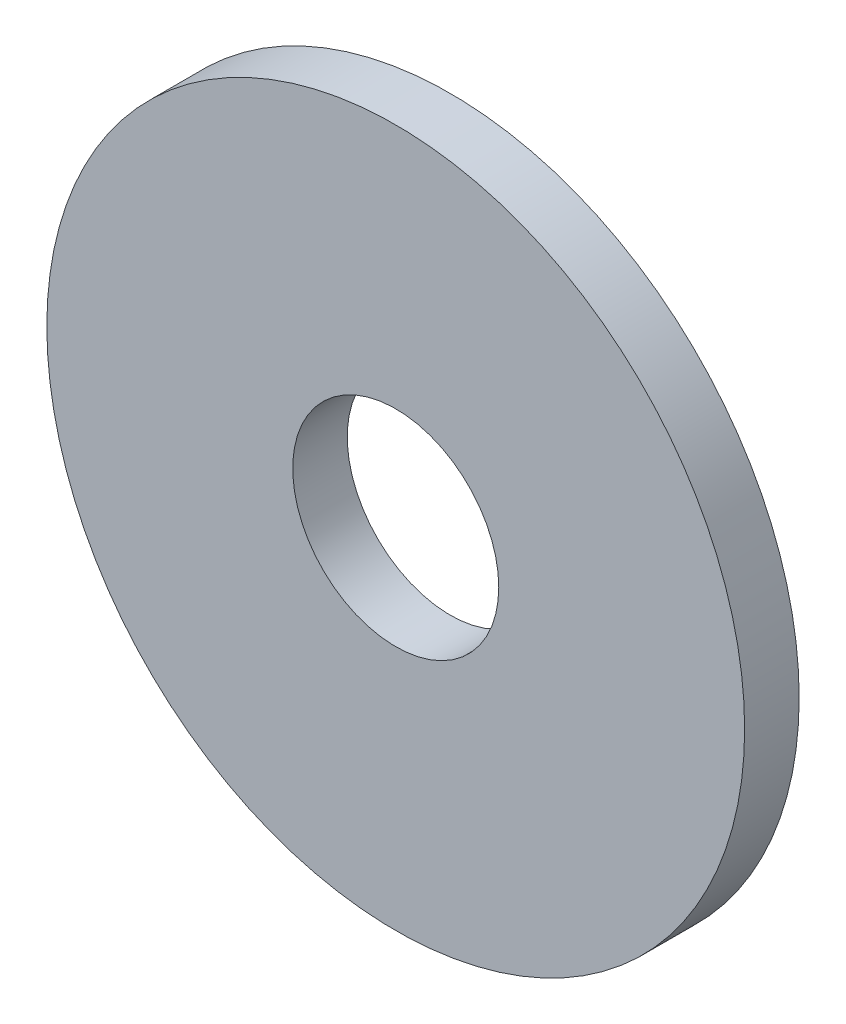
SolidWorks part; units mm, degrees
ref_plane "Front Plane" through (0, 0, 0) normal (0, 0, 1) x (1, 0, 0)
ref_plane "Top Plane" through (0, 0, 0) normal (0, 1, 0) x (1, 0, 0)
ref_plane "Right Plane" through (0, 0, 0) normal (1, 0, 0) x (0, 0, -1)
sketch "Baseplate" plane through (0, 0, 0) normal (0, 0, 1) x (1, 0, 0)
  circle A0 centre (0, 0) radius 101.6
  circle A1 centre (0, 0) radius 30
extrude "Boss-Extrude1" add sketch "Baseplate" along normal blind 15.875
